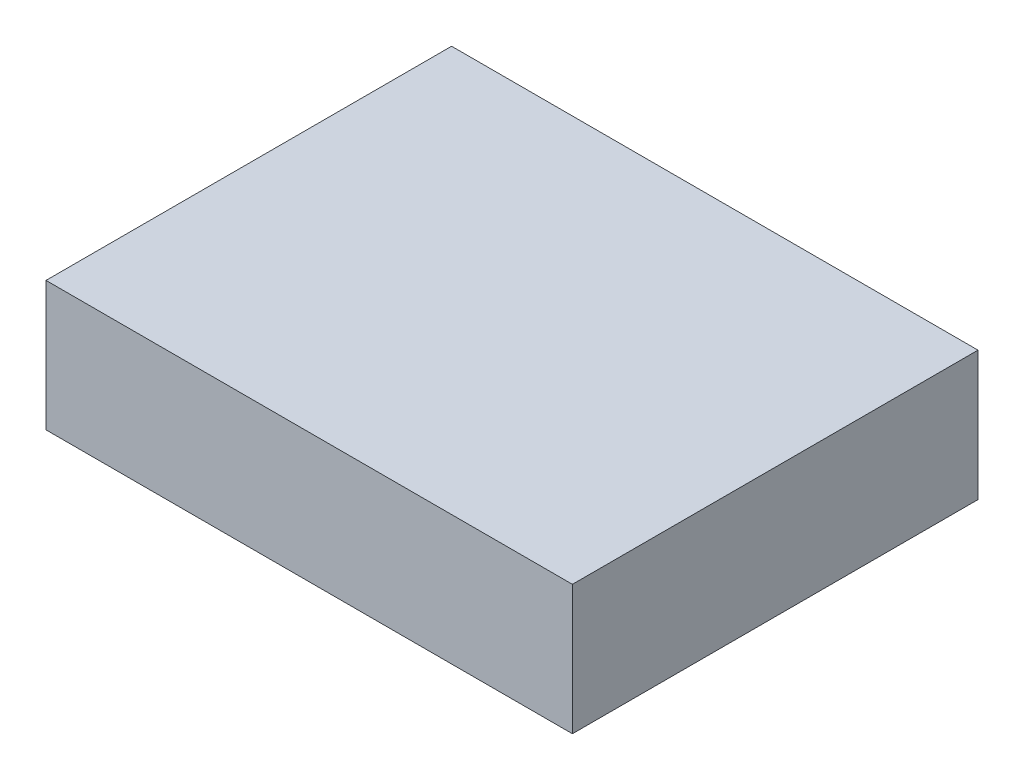
SolidWorks part; units mm, degrees
ref_plane "前视基准面" through (0, 0, 0) normal (0, 0, 1) x (1, 0, 0)
ref_plane "上视基准面" through (0, 0, 0) normal (0, 1, 0) x (1, 0, 0)
ref_plane "右视基准面" through (0, 0, 0) normal (1, 0, 0) x (0, 0, -1)
other "Configuration Table"
sketch "草图1" plane through (0, 0, 0) normal (0, 1, 0) x (1, 0, 0)
  line L1 (0, 0) -> (61, 0)
  line L2 (0, 0) -> (0, 47)
  line L3 (0, 47) -> (61, 47)
  line L4 (61, 0) -> (61, 47)
extrude "凸台-拉伸1" add sketch "草图1" along normal blind 15
